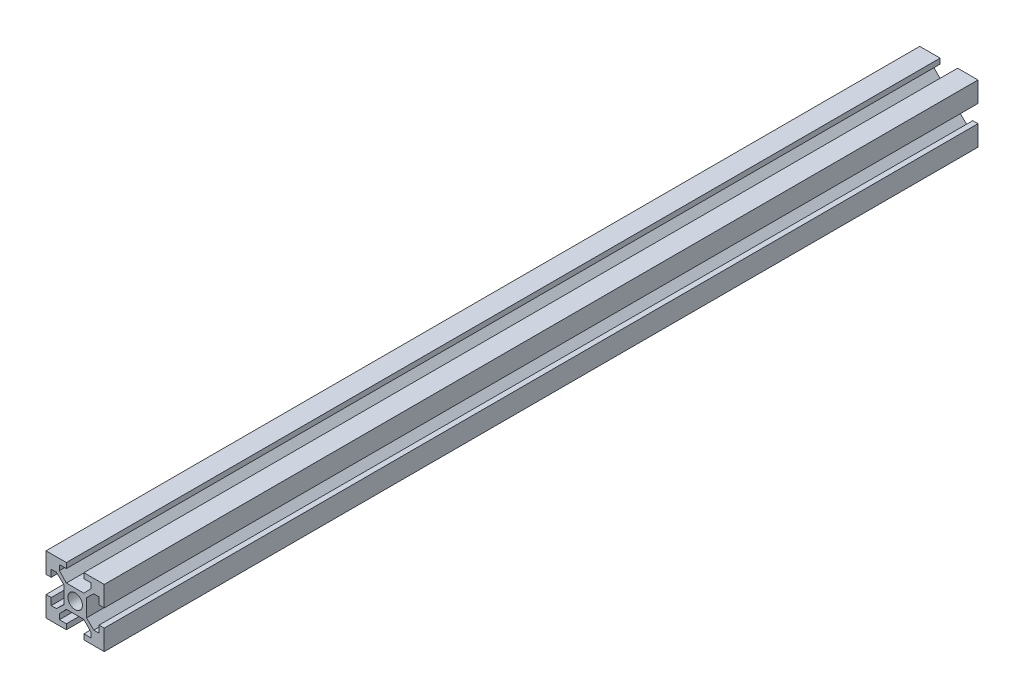
SolidWorks part; units mm, degrees
ref_plane "Front Plane" through (0, 0, 0) normal (0, 0, 1) x (1, 0, 0)
ref_plane "Top Plane" through (0, 0, 0) normal (0, 1, 0) x (1, 0, 0)
ref_plane "Right Plane" through (0, 0, 0) normal (1, 0, 0) x (0, 0, -1)
sketch "Sketch2" plane through (0, 0, 0) normal (0, 0, 1) x (1, 0, 0)
  line L0 (7, 0) -> (13, 0)
  line L1 (0, 0) -> (20, 0)
  line L2 (0, 0) -> (0, -20)
  line L3 (0, -20) -> (20, -20)
  line L4 (20, 0) -> (20, -20)
  line L5 (13, 0) -> (13, -1.8)
  line L6 (13, -1.8) -> (15.4, -1.8)
  line L7 (15.4, -1.8) -> (15.4, -3.6)
  line L8 (20, -13) -> (18.2, -13)
  line L9 (7, -6.1) -> (13, -6.1)
  line L10 (13, -6.1) -> (15.4, -3.6)
  line L18 (20, -6.6) -> (20, -12.6)
  line L46 (13.9, -6.6) -> (13.9, -12.6) [skipped]
  line L48 (20, -12.6) -> (18.2, -12.6) [skipped]
  line L49 (18.2, -12.6) -> (18.2, -15) [skipped]
  line L50 (18.2, -15) -> (16.4, -15) [skipped]
  line L51 (13.9, -12.6) -> (16.4, -15) [skipped]
  line L54 (13.4, -13.5) -> (7.4, -13.5) [skipped]
  line L55 (7.4, -17.8) -> (5, -17.8) [skipped]
  line L56 (5, -17.8) -> (5, -16) [skipped]
  line L57 (7.4, -13.5) -> (5, -16) [skipped]
  line L58 (7.4, -19.6) -> (7.4, -17.8) [skipped]
  line L61 (6.5, -13) -> (6.5, -7) [skipped]
  line L62 (6.5, -7) -> (4, -4.6) [skipped]
  line L63 (2.2, -4.6) -> (4, -4.6) [skipped]
  line L64 (2.2, -7) -> (2.2, -4.6) [skipped]
  line L65 (0.4, -7) -> (2.2, -7) [skipped]
  line L66 (7, -6.1) -> (4.6, -3.6)
  line L67 (4.6, -1.8) -> (4.6, -3.6)
  line L68 (7, -1.8) -> (4.6, -1.8)
  line L69 (7, 0) -> (7, -1.8)
  line L91 (18.2, -13) -> (18.2, -15.4)
  line L92 (18.2, -15.4) -> (16.4, -15.4)
  line L93 (13.9, -13) -> (16.4, -15.4)
  line L94 (13.9, -7) -> (13.9, -13)
  line L95 (13.9, -7) -> (16.4, -4.6)
  line L96 (18.2, -4.6) -> (16.4, -4.6)
  line L97 (18.2, -7) -> (18.2, -4.6)
  line L98 (20, -7) -> (18.2, -7)
  line L99 (20, -7) -> (20, -13)
  line L100 (13.4, -19.6) -> (7.4, -19.6) [skipped]
  line L101 (7, -20) -> (7, -18.2)
  line L102 (7, -18.2) -> (4.6, -18.2)
  line L103 (4.6, -18.2) -> (4.6, -16.4)
  line L104 (7, -13.9) -> (4.6, -16.4)
  line L105 (13, -13.9) -> (7, -13.9)
  line L106 (13, -13.9) -> (15.4, -16.4)
  line L107 (15.4, -18.2) -> (15.4, -16.4)
  line L108 (13, -18.2) -> (15.4, -18.2)
  line L109 (13, -20) -> (13, -18.2)
  line L110 (13, -20) -> (7, -20)
  line L111 (0, -7) -> (1.8, -7)
  line L112 (1.8, -7) -> (1.8, -4.6)
  line L113 (0.4, -13) -> (0.4, -7) [skipped]
  line L114 (1.8, -4.6) -> (3.6, -4.6)
  line L115 (6.1, -7) -> (3.6, -4.6)
  line L116 (6.1, -13) -> (6.1, -7)
  line L117 (6.1, -13) -> (3.6, -15.4)
  line L118 (1.8, -15.4) -> (3.6, -15.4)
  line L119 (1.8, -13) -> (1.8, -15.4)
  line L120 (0, -13) -> (1.8, -13)
  line L121 (0, -13) -> (0, -7)
  circle A1 centre (10, -10) radius 2.5
  point P8 (10, 0)
  point P18 (10, -6.1)
  point P54 (10, -10)
  dimension "D7" = 5
  dimension "D8" = 4
  dimension "D1" = 20
  dimension "D2" = 20
  dimension "D3" = 6
  dimension "D4" = 1.8
  dimension "D5" = 2.4
  dimension "D6" = 1.8
  dimension "D9" = 3.9
  dimension "D12" = 7
  dimension "D13" = 3.9
  dimension "D11" = 3.9
  dimension "D10" = 4
extrude "Boss-Extrude1" add sketch "Sketch2" along normal blind 300 contours L120 L2 L3 L101 L102 L103 L104 L105 L106 L107 L108 L109 L4 L8 L91 L92 L93 L94 L95 L96 L97 L98 L1 L5 L6 L7 L10 L9 L66 L67 L68 L69 L111 L112 L114 L115 L116 L117 L118 L119 A1
